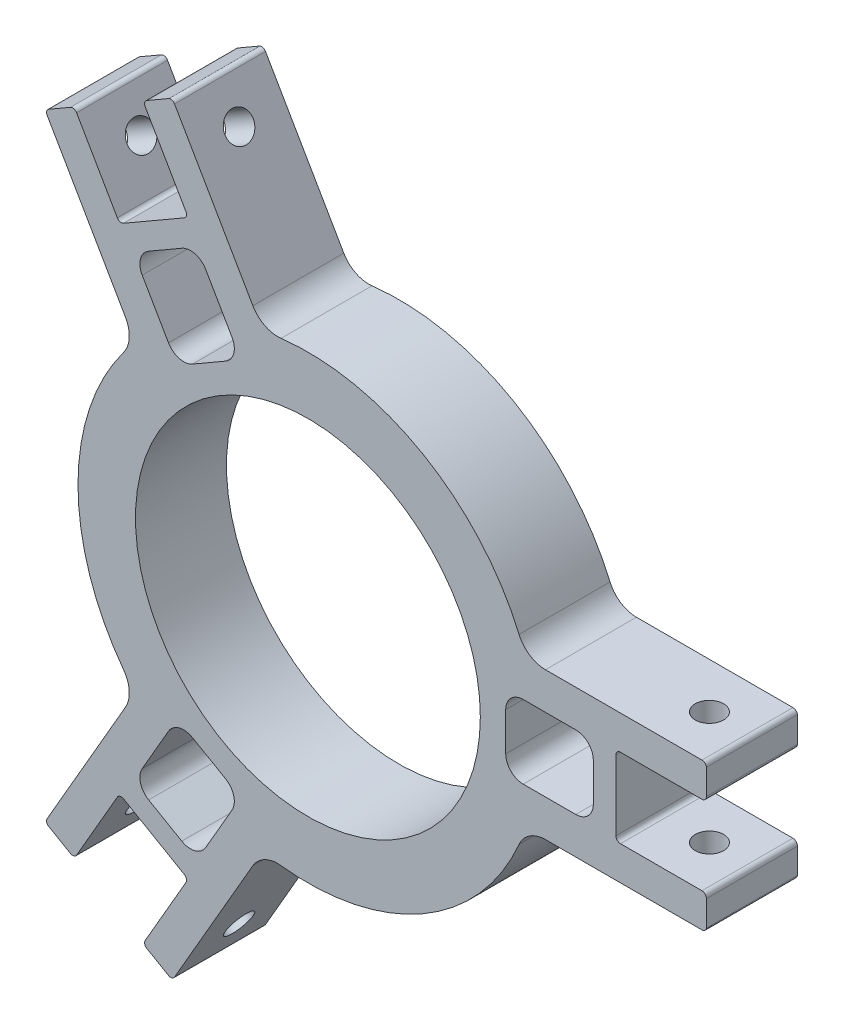
SolidWorks part; units mm, degrees
ref_plane "Front Plane" through (0, 0, 0) normal (0, 0, 1) x (1, 0, 0)
ref_plane "Top Plane" through (0, 0, 0) normal (0, 1, 0) x (1, 0, 0)
ref_plane "Right Plane" through (0, 0, 0) normal (1, 0, 0) x (0, 0, -1)
sketch "Sketch1" plane through (0, 0, 0) normal (0, 0, 1) x (1, 0, 0)
  line L0 (-92.0836, 80.8609) -> (-87.1992, 83.6809)
  line L1 (-92.4496, 79.4949) -> (-83.4496, 63.9064)
  line L2 (-85.9603, 83.253) -> (-68.6704, 53.306)
  line L6 (-105.0877, 83.8826) -> (-87.6252, 53.6367) construction
  line L8 (-114.1061, 67.003) -> (-96.8162, 37.056)
  line L9 (-108.9728, 71.1099) -> (-113.8572, 68.2899)
  line L12 (-107.6068, 70.7439) -> (-98.6068, 55.1554)
  line L13 (-97.2408, 54.7894) -> (-83.8156, 62.5404)
  line L14 (-82.0087, 35.4587) -> (-74.6908, 39.6837)
  line L15 (-91.6872, 52.2223) -> (-84.3693, 56.4473)
  line L27 (31.5639, -10.029) -> (31.5639, -15.669)
  line L43 (30.5639, -9.029) -> (12.5639, -9.029)
  line L48 (30.5739, -16.528) -> (-4.006, -16.528)
  line L49 (-90.5282, 58.6649) -> (-88.0282, 54.3348) construction
  line L50 (2.6889, -8.378) -> (-8.9181, -8.378)
  line L51 (2.6889, 7.822) -> (-8.9181, 7.822)
  line L52 (-96.8162, 37.056) -> (-68.6704, 53.306) construction
  line L53 (30.5739, 15.972) -> (-4.006, 15.972)
  line L54 (-97.2246, 30.0856) -> (-62.4296, 50.1745) construction
  line L55 (31.5639, 9.473) -> (31.5639, 15.113)
  line L56 (-74.6908, 39.6837) -> (-84.3693, 56.4473) construction
  line L57 (30.5639, 8.473) -> (12.5639, 8.473)
  line L58 (11.5639, 7.473) -> (11.5639, -8.029)
  line L59 (-12.7931, 3.947) -> (-12.7931, -4.503)
  line L60 (6.5639, 3.947) -> (6.5639, -4.503)
  line L61 (40.6827, -0.278) -> (5.7577, -0.278) construction
  line L62 (11.5639, -0.278) -> (6.5639, -0.278) construction
  line L63 (-4.006, 15.972) -> (-4.006, -16.528) construction
  line L64 (-9.8384, 19.8109) -> (-9.8384, -20.3669) construction
  line L65 (-108.9728, -71.6659) -> (-113.8572, -68.8459)
  line L66 (-107.6068, -71.2998) -> (-98.6068, -55.7114)
  line L67 (-114.1061, -67.559) -> (-96.8162, -37.612)
  line L68 (-93.1055, -47.4849) -> (-87.302, -37.433)
  line L69 (-79.0759, -55.5849) -> (-73.2724, -45.533)
  line L70 (-85.9603, -83.809) -> (-68.6704, -53.862)
  line L71 (-92.0836, -81.4169) -> (-87.1992, -84.2369)
  line L72 (-92.4496, -80.0509) -> (-83.4496, -64.4624)
  line L73 (-83.8156, -63.0964) -> (-97.2408, -55.3454)
  line L74 (-74.6908, -40.2396) -> (-82.0087, -36.0146)
  line L75 (-84.3693, -57.0032) -> (-91.6872, -52.7782)
  line L76 (-105.0877, -84.4386) -> (-87.6252, -54.1926) construction
  line L77 (-90.5282, -59.2209) -> (-88.0282, -54.8907) construction
  line L78 (-68.6704, -53.862) -> (-96.8162, -37.612) construction
  line L79 (-62.4296, -50.7304) -> (-97.2246, -30.6416) construction
  line L80 (-84.3693, 56.4473) -> (-74.6908, 39.6837) construction
  line L81 (-79.0759, 55.0289) -> (-73.2724, 44.977)
  line L82 (-93.1055, 46.9289) -> (-87.302, 36.877)
  arc A0 (-68.6704, 53.306) -> (-62.4296, 50.1745) centre (-63.1711, 56.481) ccw
  arc A1 (-92.4496, 79.4949) -> (-92.0836, 80.8609) centre (-91.5836, 79.9949) cw
  arc A2 (-85.9603, 83.253) -> (-87.1992, 83.6809) centre (-86.8263, 82.753) ccw
  arc A3 (-83.8156, 62.5404) -> (-83.4496, 63.9064) centre (-84.3156, 63.4064) ccw
  arc A8 (-79.0759, 55.0289) -> (-84.3693, 56.4473) centre (-82.4318, 53.0914) ccw
  arc A9 (-73.2724, 44.977) -> (-74.6908, 39.6837) centre (-76.6283, 43.0395) cw
  arc A10 (-93.1055, 46.9289) -> (-91.6872, 52.2223) centre (-89.7497, 48.8664) cw
  arc A11 (-87.302, 36.877) -> (-82.0087, 35.4587) centre (-83.9462, 38.8145) ccw
  arc A12 (-96.8162, 37.056) -> (-97.2246, 30.0856) centre (-102.3155, 33.881) cw
  arc A13 (-114.1061, 67.003) -> (-113.8572, 68.2899) centre (-113.2401, 67.503) cw
  arc A14 (-107.6068, 70.7439) -> (-108.9728, 71.1099) centre (-108.4728, 70.2439) ccw
  arc A16 (-97.2408, 54.7894) -> (-98.6068, 55.1554) centre (-97.7408, 55.6554) cw
  circle A49 centre (-56.4975, -0.278) radius 38.1
  arc A50 (-97.2246, 30.0856) -> (-96.5568, -31.5173) centre (-56.4975, -0.278) ccw
  arc A51 (-8.9086, 17.4966) -> (-62.4296, 50.1745) centre (-56.4975, -0.278) ccw
  arc A53 (-4.006, -16.528) -> (-9.8384, -20.3669) centre (-4.006, -22.878) ccw
  arc A54 (30.5639, -9.029) -> (31.5639, -10.029) centre (30.5639, -10.029) cw
  arc A55 (30.5739, -16.528) -> (31.5639, -15.669) centre (30.5739, -15.528) ccw
  arc A56 (11.5639, -8.029) -> (12.5639, -9.029) centre (12.5639, -8.029) ccw
  arc A57 (2.6889, -8.378) -> (6.5639, -4.503) centre (2.6889, -4.503) ccw
  arc A58 (-8.9181, -8.378) -> (-12.7931, -4.503) centre (-8.9181, -4.503) cw
  arc A59 (2.6889, 7.822) -> (6.5639, 3.947) centre (2.6889, 3.947) cw
  arc A60 (-8.9181, 7.822) -> (-12.7931, 3.947) centre (-8.9181, 3.947) ccw
  arc A61 (-4.006, 15.972) -> (-9.8384, 19.8109) centre (-4.006, 22.322) cw
  arc A62 (30.5739, 15.972) -> (31.5639, 15.113) centre (30.5739, 14.972) cw
  arc A63 (30.5639, 8.473) -> (31.5639, 9.473) centre (30.5639, 9.473) ccw
  arc A64 (11.5639, 7.473) -> (12.5639, 8.473) centre (12.5639, 7.473) cw
  circle A65 centre (-56.4975, -0.278) radius 38.1
  arc A66 (-9.8384, 19.8109) -> (-63.522, 50.034) centre (-56.4975, -0.278) ccw
  arc A67 (-64.8987, -50.3785) -> (-9.8384, -20.3669) centre (-56.4975, -0.278) ccw
  arc A68 (-96.8162, -37.612) -> (-97.2246, -30.6416) centre (-102.3155, -34.437) ccw
  arc A69 (-107.6068, -71.2998) -> (-108.9728, -71.6659) centre (-108.4728, -70.7998) cw
  arc A70 (-114.1061, -67.559) -> (-113.8572, -68.8459) centre (-113.2401, -68.059) ccw
  arc A71 (-97.2408, -55.3454) -> (-98.6068, -55.7114) centre (-97.7408, -56.2114) ccw
  arc A72 (-93.1055, -47.4849) -> (-91.6872, -52.7782) centre (-89.7497, -49.4224) ccw
  arc A73 (-87.302, -37.433) -> (-82.0087, -36.0146) centre (-83.9462, -39.3705) cw
  arc A74 (-79.0759, -55.5849) -> (-84.3693, -57.0032) centre (-82.4318, -53.6474) cw
  arc A75 (-73.2724, -45.533) -> (-74.6908, -40.2396) centre (-76.6283, -43.5955) ccw
  arc A76 (-68.6704, -53.862) -> (-62.4296, -50.7304) centre (-63.1711, -57.037) cw
  arc A77 (-85.9603, -83.809) -> (-87.1992, -84.2369) centre (-86.8263, -83.309) cw
  arc A78 (-92.4496, -80.0509) -> (-92.0836, -81.4169) centre (-91.5836, -80.5509) ccw
  arc A79 (-83.8156, -63.0964) -> (-83.4496, -64.4624) centre (-84.3156, -63.9624) cw
  circle A80 centre (-56.4975, -0.278) radius 38.1
  arc A81 (-62.4296, -50.7304) -> (-9.4138, -19.3506) centre (-56.4975, -0.278) ccw
  arc A82 (-95.6852, 32.0479) -> (-97.2246, -30.6416) centre (-56.4975, -0.278) ccw
  point P135 (-56.4975, -0.278)
  dimension "D5" = 1
  dimension "D6" = 1
  dimension "D17" = 50.8
  dimension "D33" = 6.35
  dimension "D9" = 5.64
  dimension "D2" = 90
  dimension "D3" = 18
  dimension "D4" = 90
  dimension "D7" = 1
  dimension "1" = 1
  dimension "D8" = 3
  dimension "D16" = 43.7044
  dimension "D38" = 32.5
  dimension "D48" = 34.5798
  dimension "5" = 5
extrude "Boss-Extrude1" add sketch "Sketch1" along normal blind 20.1
sketch "Sketch4" plane through (-28.4206, -16.4086, 0) normal (0.866, 0.5, 0) x (0, 0, -1)
  line L0 (-20.1, 115.0794) -> (0, 115.0794) construction
  line L2 (-10.05, 115.0794) -> (-10.05, 80.4996) construction
  line L3 (-20.1, 80.4996) -> (0, 80.4996) construction
  circle A0 centre (-10.05, 106.6794) radius 3.125
  dimension "D1" = 8.4
  dimension "D3" = 6.25
extrude "Cut-Extrude3" cut sketch "Sketch4" against normal through all
ref_plane "Plane1" through (-87.1992, 83.6809, 20.1) normal (0, 0, -1) x (-1, 0, 0)
sketch "Sketch6" plane through (-28.1799, 16.2696, 0) normal (0.866, -0.5, 0) x (0, 0, -1)
  line L0 (-10.05, -80.9811) -> (-10.05, -115.5609) construction
  line L1 (-20.1, -115.5609) -> (0, -115.5609) construction
  line L2 (-20.1, -80.9811) -> (0, -80.9811) construction
  circle A0 centre (-10.05, -107.1609) radius 3.125
  dimension "D1" = 6.25
  dimension "D2" = 8.4
extrude "Cut-Extrude4" cut sketch "Sketch6" against normal through all
sketch "Sketch7" plane through (0, 15.972, 0) normal (0, 1, 0) x (1, 0, 0)
  line L0 (30.5739, -20.1) -> (30.5739, 0) construction
  line L1 (-4.006, -10.05) -> (30.5739, -10.05) construction
  line L2 (-4.006, -20.1) -> (-4.006, 0) construction
  circle A0 centre (22.1739, -10.05) radius 3.125
  dimension "D1" = 6.25
  dimension "8.4" = 8.4
extrude "Cut-Extrude5" cut sketch "Sketch7" against normal through all
